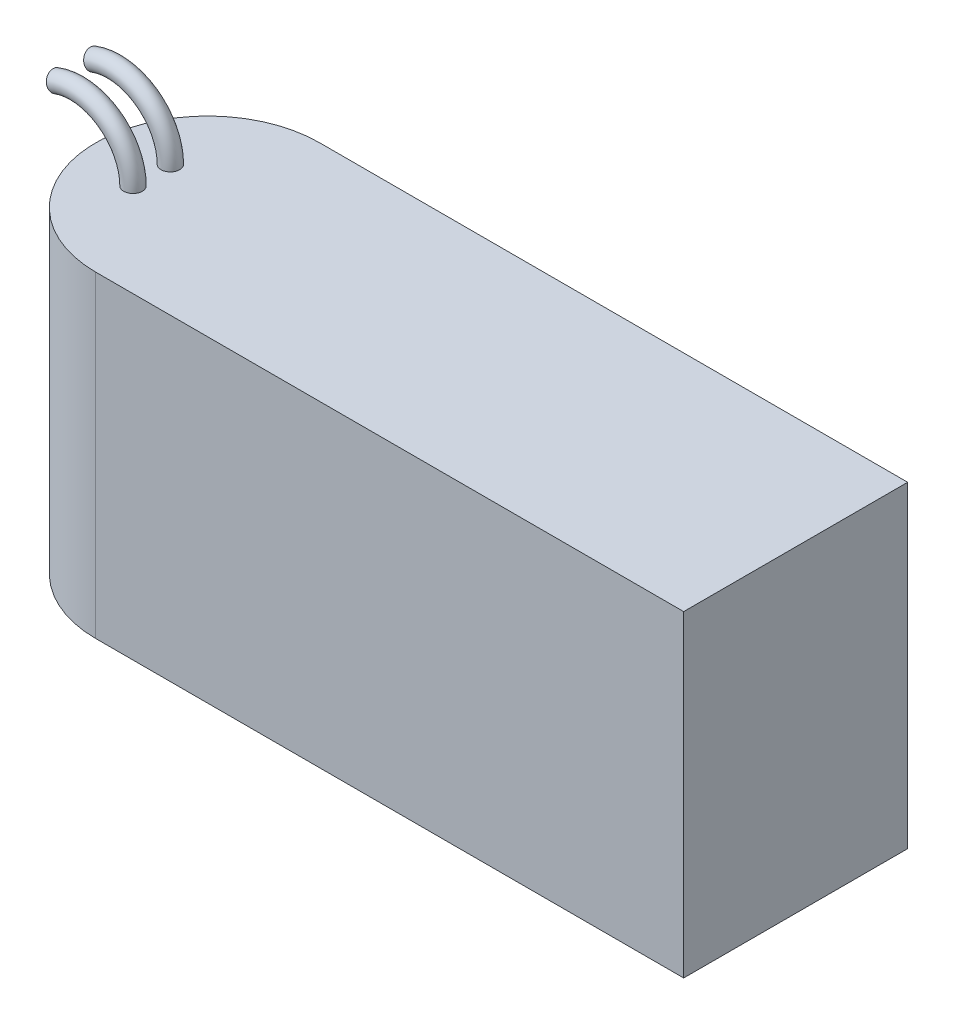
SolidWorks part; units mm, degrees
ref_plane "Front Plane" through (0, 0, 0) normal (0, 0, 1) x (1, 0, 0)
ref_plane "Top Plane" through (0, 0, 0) normal (0, 1, 0) x (1, 0, 0)
ref_plane "Right Plane" through (0, 0, 0) normal (1, 0, 0) x (0, 0, -1)
sketch "Sketch1" plane through (0, 0, 0) normal (0, 1, 0) x (1, 0, 0)
  line L0 (0, 0) -> (63, 0)
  line L1 (63, 0) -> (63, 24)
  line L2 (63, 24) -> (0, 24)
  arc A0 (0, 24) -> (0, 0) centre (0, 12) ccw
  point P6 (-12, 12)
  dimension "D1" = 24
  dimension "D2" = 75
extrude "Boss-Extrude1" add sketch "Sketch1" along normal blind 34
ref_plane "Plane1" through (0, 0, -14) normal (0, 0, -1) x (-1, 0, 0)
sketch "Sketch21" plane through (0, 0, -14) normal (0, 0, -1) x (-1, 0, 0)
  line L0 (6, 34) -> (6, 43.3683) construction
  line L1 (12, 34) -> (0, 34) construction
  line L2 (6, 38.6842) -> (23.7734, 38.6842) construction
  line L3 (6, 34) -> (6, 16.0408) construction
  arc A0 (6, 34) -> (14.2268, 39.6495) centre (12.0533, 34) cw
  point P9 (17.6228, 39.9406)
  point P10 (6, 34)
  point P11 (14.2268, 39.6495)
sweep "Sweep2" add path "Sketch21" circular profile diameter 2 parameters "D3"=2
pattern_linear "LPattern1" count 2 spacing 4 along (0, 0, 1) of "Sweep2"
